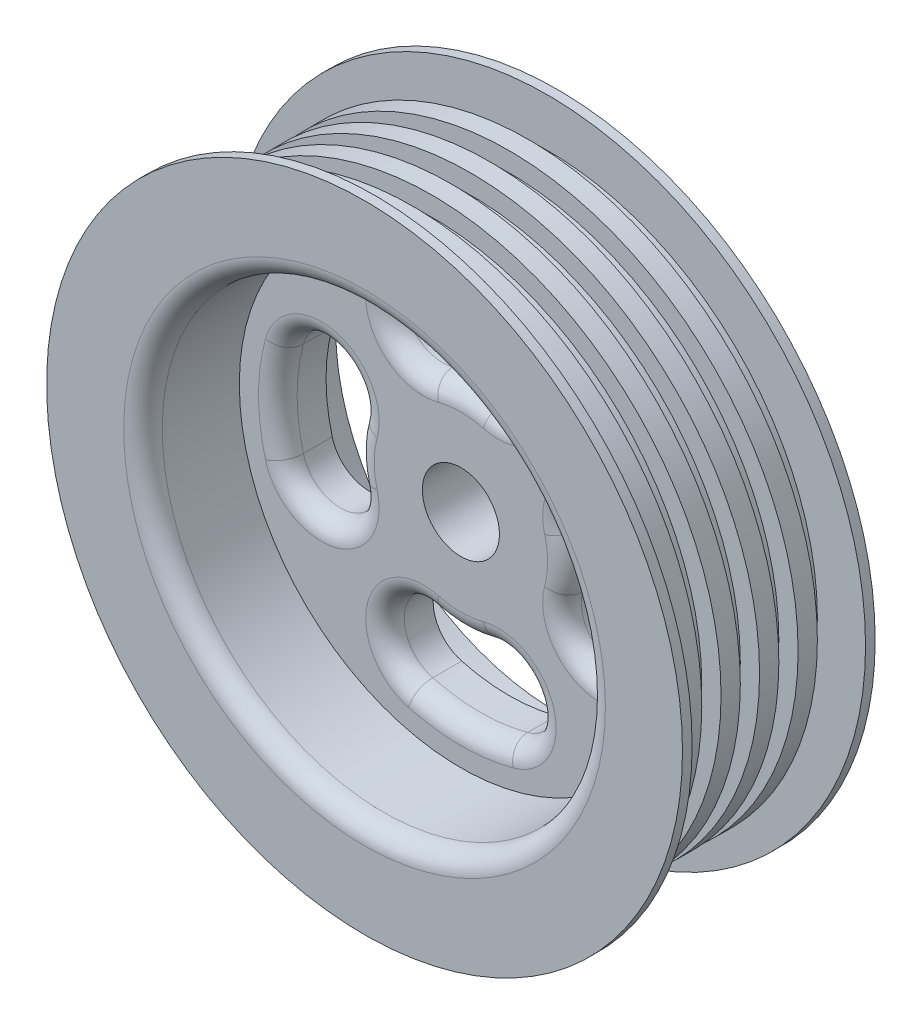
SolidWorks part; units mm, degrees
ref_plane "Front Plane" through (0, 0, 0) normal (0, 0, 1) x (1, 0, 0)
ref_plane "Top Plane" through (0, 0, 0) normal (0, 1, 0) x (1, 0, 0)
ref_plane "Right Plane" through (0, 0, 0) normal (1, 0, 0) x (0, 0, -1)
sketch "Sketch1" plane through (0, 0, 0) normal (0, 0, 1) x (1, 0, 0)
  circle A0 centre (0, 0) radius 33
  dimension "D1" = 66
extrude "Boss-Extrude1" add sketch "Sketch1" along normal blind 20
shell "Shell1" thickness 10
sketch "Sketch2" plane through (0, 0, 10) normal (0, 0, 1) x (1, 0, 0)
  circle A0 centre (0, 0) radius 4
  dimension "D1" = 8
extrude "Cut-Extrude1" cut sketch "Sketch2" against normal through all
sketch "Sketch3" plane through (0, 0, 0) normal (0, 1, 0) x (1, 0, 0)
  line L0 (33, -20) -> (33, 0) construction
  line L1 (33, -1) -> (30, -1)
  line L2 (33, -1) -> (33, -19)
  line L3 (33, -19) -> (30, -19)
  line L4 (30, -1) -> (30, -19)
  line L5 (33, 0) -> (-33, 0) construction
  line L6 (-33, -20) -> (33, -20) construction
  dimension "D1" = 1
  dimension "D2" = 1
  dimension "D3" = 3
revolve "Cut-Revolve1" cut sketch "Sketch3" angle 360 about axis through (0, 0, 20) along (0, 0, -1)
sketch "Sketch4" plane through (0, 0, 0) normal (0, 1, 0) x (1, 0, 0)
  line L0 (-30, -1) -> (30, -1) construction
  line L1 (28, -1) -> (30, -1)
  line L2 (28, -1) -> (28, -3)
  line L3 (28, -3) -> (30, -3)
  line L4 (30, -1) -> (30, -3)
  line L5 (30, -19) -> (30, -1) construction
  dimension "D1" = 2
  dimension "D2" = 2
revolve "Cut-Revolve2" cut sketch "Sketch4" angle 360 about axis through (0, 0, 20) along (0, 0, -1)
pattern_linear "LPattern1" count 5 spacing 4 along (0, 0, 1) of "Cut-Revolve2"
sketch "Sketch5" plane through (0, 0, 0) normal (0, 0, -1) x (-1, 0, 0)
  circle A0 centre (0, 0) radius 23 construction
  circle A1 centre (0, 0) radius 23
  circle A2 centre (0, 0) radius 7.5
  dimension "D1" = 15
extrude "Cut-Extrude2" cut sketch "Sketch5" against normal blind 5
sketch "Sketch6" plane through (0, 0, 10) normal (0, 0, 1) x (1, 0, 0)
  line L0 (0, 0) -> (0, 40.3037) construction
  line L1 (-3.8823, 14.4889) -> (0, 0) construction
  line L2 (0, 0) -> (3.8823, 14.4889) construction
  arc A0 (-3.8823, 14.4889) -> (3.8823, 14.4889) centre (0, 0) cw construction
  arc A1 (4.9176, 18.3526) -> (-4.9176, 18.3526) centre (0, 0) ccw
  arc A2 (2.847, 10.6252) -> (-2.847, 10.6252) centre (0, 0) ccw
  arc A3 (2.847, 10.6252) -> (4.9176, 18.3526) centre (3.8823, 14.4889) ccw
  arc A4 (-4.9176, 18.3526) -> (-2.847, 10.6252) centre (-3.8823, 14.4889) ccw
  point P4 (0, 15)
  dimension "D2" = 4
  dimension "D3" = 15
  dimension "D1" = 30
extrude "Cut-Extrude3" cut sketch "Sketch6" against normal blind 5
pattern_circular "CirPattern1" count 4 over 360 about axis through (0, 0, 0) along (0, 0, 1) of "Cut-Extrude3"
fillet "Fillet1" radius 2 16 edges at (-19, 0, 10) (-13.4536, 7.746, 10) (-11, 0, 10) (7.746, -13.4536, 10) (0, -19, 10) (-7.746, -13.4536, 10) (13.4536, 7.746, 10) (19, 0, 10) (13.4536, -7.746, 10) (0, 11, 10) (-7.746, 13.4536, 10) (0, 19, 10) (-13.4536, -7.746, 10) (0, -11, 10) (11, 0, 10) (7.746, 13.4536, 10)
fillet "Fillet2" radius 2 1 edges at (23, 0, 20)
